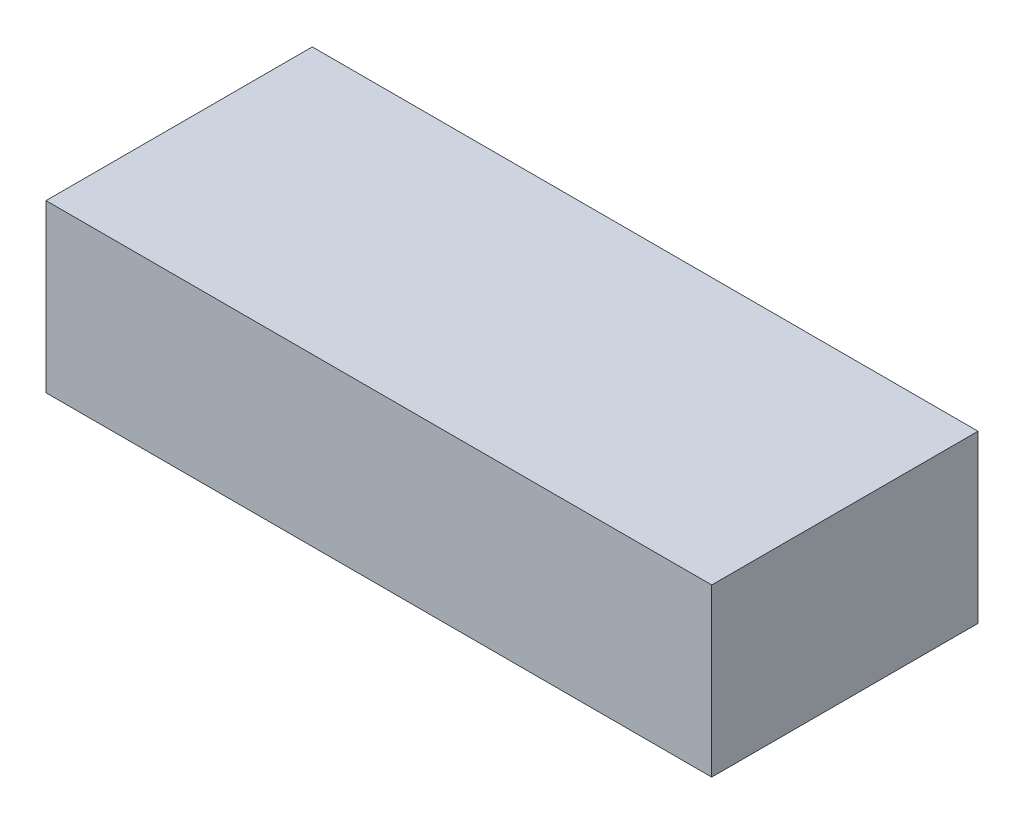
SolidWorks part; units mm, degrees
ref_plane "Front Plane" through (0, 0, 0) normal (0, 0, 1) x (1, 0, 0)
ref_plane "Top Plane" through (0, 0, 0) normal (0, 1, 0) x (1, 0, 0)
ref_plane "Right Plane" through (0, 0, 0) normal (1, 0, 0) x (0, 0, -1)
sketch "SK_P01_Yadapter" plane through (0, 0, 0) normal (0, 1, 0) x (1, 0, 0)
  line L0 (-20, -8) -> (20, -8)
  line L1 (20, -8) -> (20, 8)
  line L2 (20, 8) -> (-20, 8)
  line L3 (-20, 8) -> (-20, -8)
extrude "P01_Yadapter" add sketch "SK_P01_Yadapter" along normal blind 10
